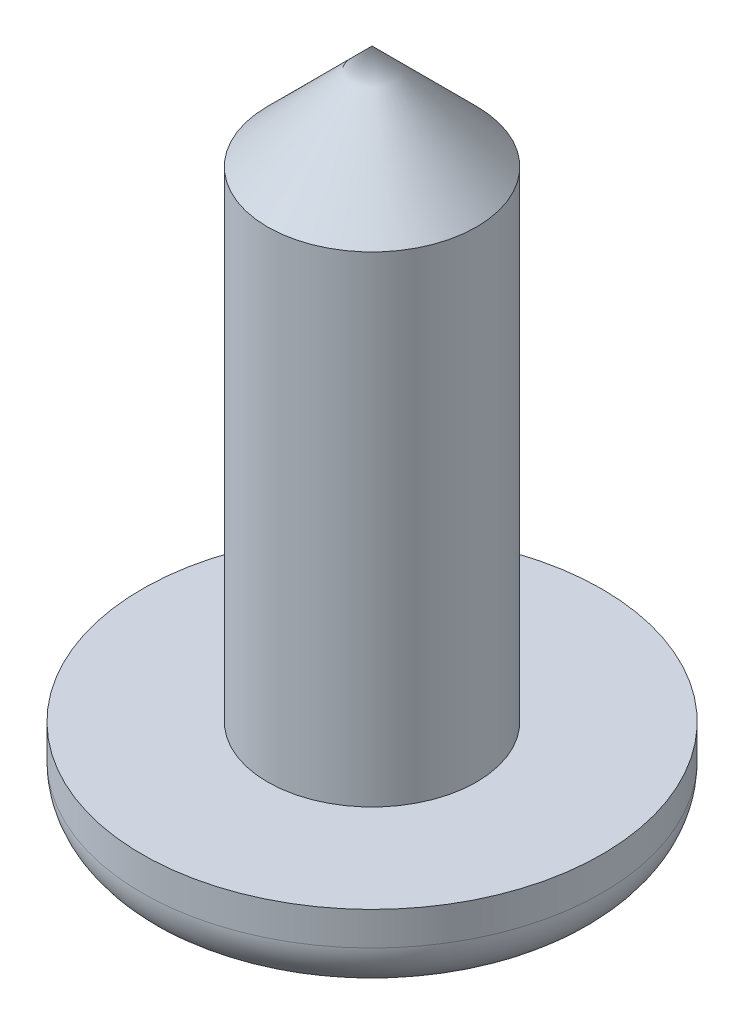
SolidWorks part; units mm, degrees
ref_plane "Front Plane" through (0, 0, 0) normal (0, 0, 1) x (1, 0, 0)
ref_plane "Top Plane" through (0, 0, 0) normal (0, 1, 0) x (1, 0, 0)
ref_plane "Right Plane" through (0, 0, 0) normal (1, 0, 0) x (0, 0, -1)
sketch "Sketch1" plane through (0, 0, 0) normal (0, 0, 1) x (1, 0, 0)
  line L0 (0, 0) -> (0, 8)
  line L1 (0, 8) -> (-1.25, 6.75)
  line L2 (-1.25, 6.75) -> (-1.25, 1)
  line L3 (-1.25, 1) -> (-2.75, 1)
  line L4 (-2.75, 1) -> (-2.75, 0.6)
  line L5 (-2.15, 0) -> (0, 0)
  line L6 (0, 8) -> (0, 57.6873) construction
  arc A0 (-2.75, 0.6) -> (-2.15, 0) centre (-2.15, 0.6) ccw
  point P9 (-2.75, 0)
  dimension "D5" = 0.6
  dimension "D1" = 45
  dimension "D2" = 2.5
  dimension "D3" = 5.5
  dimension "D4" = 1
  dimension "D6" = 8
revolve "Revolve1" add sketch "Sketch1" angle 360 about L6
sketch "Sketch2" plane through (0, 0, 0) normal (0, -1, 0) x (1, 0, 0)
  line L1 (-0.25, -1) -> (0.25, -1)
  line L2 (-0.25, -1) -> (-0.25, 1)
  line L3 (-0.25, 1) -> (0.25, 1)
  line L4 (0.25, -1) -> (0.25, 1)
  line L5 (-0.25, -1) -> (0.25, 1) construction
  line L6 (-0.25, 1) -> (0.25, -1) construction
  line L7 (-1, 0.25) -> (1, 0.25)
  line L8 (-1, 0.25) -> (-1, -0.25)
  line L9 (-1, -0.25) -> (1, -0.25)
  line L10 (1, 0.25) -> (1, -0.25)
  line L11 (-1, 0.25) -> (1, -0.25) construction
  line L12 (-1, -0.25) -> (1, 0.25) construction
  point P0 (0, 0)
  point P6 (0, 0)
  dimension "D1" = 2
  dimension "D2" = 0.5
extrude "Cut-Extrude1" cut sketch "Sketch2" against normal blind 0.8 draft 20 contours L2 L7 L4 L3 | L2 L9 L4 L7 | L10 L7 L4 L9 | L9 L2 L1 L4 | L8 L9 L2 L7
other "Freeze***"
